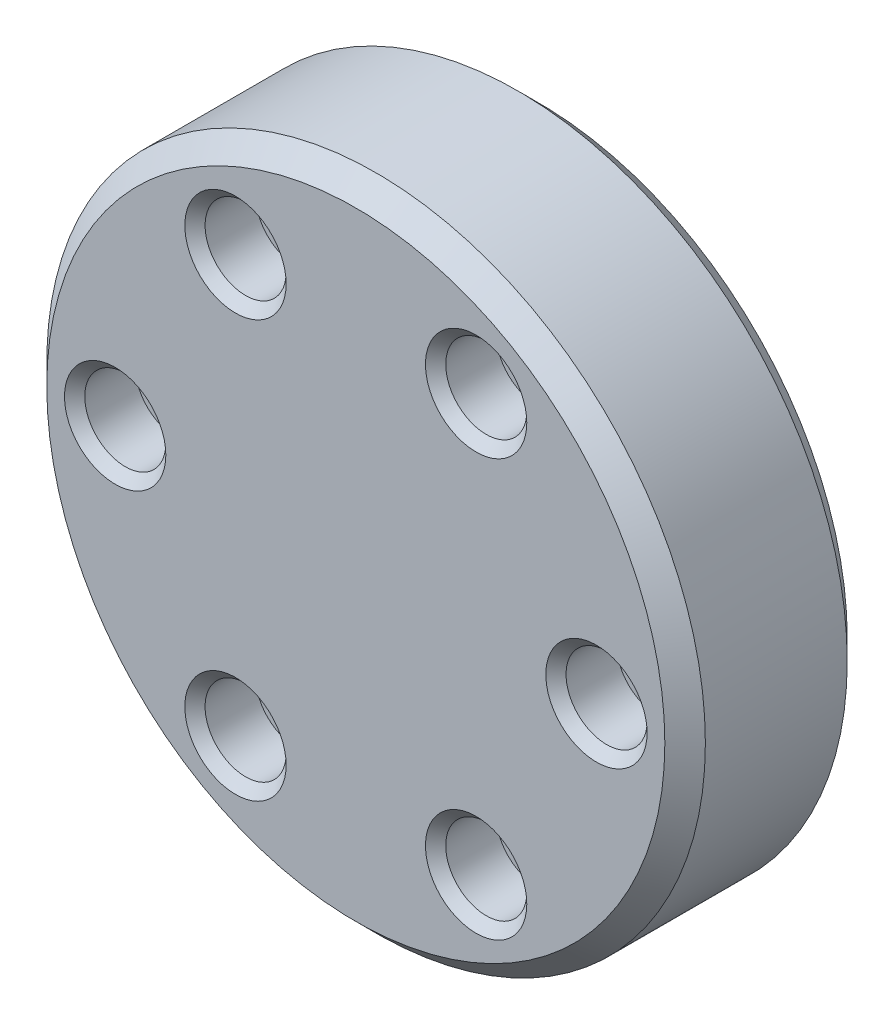
SolidWorks part; units mm, degrees
ref_plane "正面" through (0, 0, 0) normal (0, 0, 1) x (1, 0, 0)
ref_plane "平面" through (0, 0, 0) normal (0, 1, 0) x (1, 0, 0)
ref_plane "右側面" through (0, 0, 0) normal (1, 0, 0) x (0, 0, -1)
sketch "ｽｹｯﾁ1" plane through (0, 0, 0) normal (0, 0, 1) x (1, 0, 0)
  circle A0 centre (0, 0) radius 32.5
  dimension "D1" = 65
extrude "ﾎﾞｽ - 押し出し1" add sketch "ｽｹｯﾁ1" along normal mid plane 18
chamfer "面取り1" distance 2 angle 45 2 edges at (32.5, 0, -9) (32.5, 0, 9)
sketch "ｽｹｯﾁ3" plane through (0, 0, 0) normal (0, 0, 1) x (1, 0, 0)
  circle A0 centre (11.875, 20.5681) radius 2.6 construction
  circle A1 centre (11.875, 20.5681) radius 2.6
extrude "ｶｯﾄ - 押し出し1" cut sketch "ｽｹｯﾁ3" against normal through all both and the other way through all
sketch "ｽｹｯﾁ4" plane through (0, 0, 0) normal (0, 0, 1) x (1, 0, 0)
  circle A0 centre (11.875, 20.5681) radius 4
  dimension "D1" = 8
extrude "ｶｯﾄ - 押し出し2" cut sketch "ｽｹｯﾁ4" against normal blind 6 from surface at 9 starting at face at (14.475, 20.5681, 9)
chamfer "面取り2" distance 1 angle 45 1 edges at (15.875, 20.5681, 9)
pattern_circular "円形ﾊﾟﾀｰﾝ1" count 6 over 360 about axis through (0, 0, 0) along (0, 0, 1) of "ｶｯﾄ - 押し出し1", "ｶｯﾄ - 押し出し2", "面取り2"
sketch "ｽｹｯﾁ5" plane through (0, 0, -9) normal (0, 0, -1) x (-1, 0, 0)
  circle A0 centre (0, 0) radius 28.4 construction
  circle A1 centre (0, 0) radius 28.4
extrude "ｶｯﾄ - 押し出し3" cut sketch "ｽｹｯﾁ5" against normal blind 10
